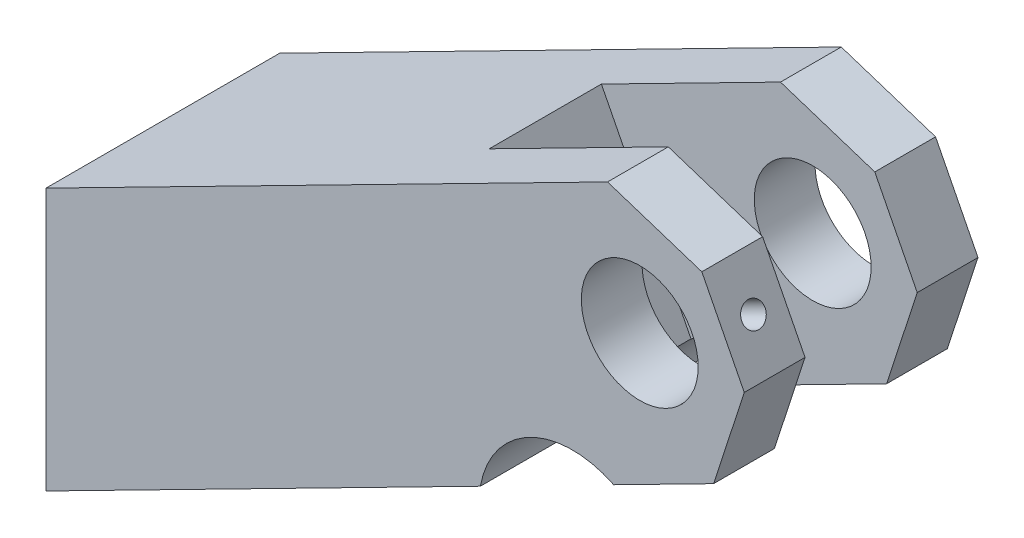
SolidWorks part; units mm, degrees
material "Masterteil Geometrie"
ref_plane "Vorne" through (0, 0, 0) normal (0, 0, 1) x (1, 0, 0)
ref_plane "Oben" through (0, 0, 0) normal (0, 1, 0) x (1, 0, 0)
ref_plane "Rechts" through (0, 0, 0) normal (1, 0, 0) x (0, 0, -1)
sketch "Skizze1" plane through (0, 0, 0) normal (0, 0, 1) x (1, 0, 0)
  line L0 (0, 0) -> (120.1288, 61.2087)
  line L1 (120.1288, 61.2087) -> (140.3038, 54.6535)
  line L2 (140.3038, 54.6535) -> (149.3836, 36.8333)
  line L3 (149.3836, 36.8333) -> (142.8283, 16.6584)
  line L4 (142.8283, 16.6584) -> (121.4442, 5.7626)
  line L5 (92.932, -8.7651) -> (0, -56.1163)
  line L6 (0, -56.1163) -> (0, 0)
  arc A0 (121.4442, 5.7626) -> (92.932, -8.7651) centre (112.636, -12.1933) ccw
  dimension "D3" = 20
  dimension "D4" = 8
  dimension "D9" = 55
  dimension "D1" = 45
  dimension "D2" = 45
  dimension "D5" = 63
  dimension "D6" = 15
  dimension "D7" = 15
  dimension "D8" = 50
  dimension "D10" = 175.3
extrude "Aufsatz-Linear austragen1" add sketch "Skizze1" along normal mid plane 50
sketch "Skizze2" plane through (0, 0, 0) normal (0, 0, 1) x (1, 0, 0)
  line L0 (133.4939, 68.0185) -> (81.8155, 41.6871)
  line L1 (120.1288, 61.2087) -> (0, 0) construction
  line L2 (81.8155, 41.6871) -> (104.5151, -2.8632)
  line L3 (104.5151, -2.8632) -> (156.1934, 23.4682)
  line L4 (156.1934, 23.4682) -> (133.4939, 68.0185)
  line L5 (149.3836, 36.8333) -> (140.3038, 54.6535) construction
  line L6 (121.4442, 5.7626) -> (142.8283, 16.6584) construction
  dimension "D1" = 58
extrude "Schnitt-Linear austragen1" cut sketch "Skizze2" against normal mid plane 24
hole_wizard "Ø25.0 (25) Durchmesser Bohrung1" positions "Skizze3" profile "Skizze4" hole size "Ø25.0" standard "Gabler-Normteile" end condition through all
sketch "Skizze3" plane through (0, 0, 25) normal (0, 0, 1) x (1, 0, 0)
  line L0 (149.3836, 36.8333) -> (140.3038, 54.6535) construction
  line L1 (144.8437, 45.7434) -> (127.0236, 36.6636) construction
  point P0 (127.0236, 36.6636)
  dimension "D1" = 20
sketch "Skizze4" plane through (127.0236, 36.6636, 25) normal (1, 0, 0) x (0, -1, 0)
  line L0 (0, 0) -> (0, 50)
  line L1 (0, 50) -> (12.5, 50)
  line L2 (12.5, 50) -> (12.5, 0)
  line L5 (12.5, 0) -> (0, 0)
  line L11 (0, -6.35) -> (0, 107.95) construction
  dimension "Bohrerdurchmesser" = 25
  dimension "Bohrungstiefe" = 50
hole_wizard "M6 Gewindebohrung1" positions "Skizze5" profile "Skizze7" tap size "M6" standard "Gabler-Normteile"
sketch "Skizze5" plane through (133.4939, 68.0185, 0) normal (0.891, 0.454, 0) x (0, 0, -1)
  line L0 (-25, -15) -> (-12, -15) construction
  line L1 (-25, -35) -> (-25, -15) construction
  point P0 (-18.5, -25)
  point P6 (-18.5, -15)
  point P9 (-25, -25)
sketch "Skizze7" plane through (144.8437, 45.7434, 18.5) normal (0, 0, 1) x (-0.454, 0.891, 0)
  line L0 (0, 0) -> (0, 18.5022)
  line L1 (0, 18.5022) -> (2.5, 17)
  line L2 (2.5, 17) -> (2.5, 0)
  line L5 (2.5, 0) -> (0, 0)
  line L10 (0, 18.5022) -> (-2.5, 17) construction
  line L11 (0, -6.35) -> (0, 107.95) construction
  dimension "Bohrerdurchmesser" = 5
  dimension "Bohrungstiefe" = 17
  dimension "Spitzenwinkel" = 118
cosmetic thread "Bohrungsgewinde1" parameters "D1"=7.7526, "D2"=6
hole_wizard "M12 Gewindebohrung1" positions "Skizze8" profile "Skizze9" tap size "M12" standard "Gabler-Normteile"
sketch "Skizze8" plane through (0, 0, 0) normal (-1, 0, 0) x (0, 0, 1)
  line L0 (0, 0) -> (0, -23.4984) construction
  line L2 (25, 0) -> (-25, 0) construction
  point P0 (-12.5, -12)
  point P2 (12.5, -12)
  point P4 (0, -32)
  dimension "D1" = 25
  dimension "D2" = 12
  dimension "D3" = 20
sketch "Skizze9" plane through (0, -12, -12.5) normal (0, 1, 0) x (0, 0, 1)
  line L0 (0, 0) -> (0, 28.0644)
  line L1 (0, 28.0644) -> (5.1, 25)
  line L2 (5.1, 25) -> (5.1, 0)
  line L5 (5.1, 0) -> (0, 0)
  line L10 (0, 28.0644) -> (-5.1, 25) construction
  line L11 (0, -6.35) -> (0, 107.95) construction
  dimension "Bohrerdurchmesser" = 10.2
  dimension "Bohrungstiefe" = 25
  dimension "Spitzenwinkel" = 118
cosmetic thread "Bohrungsgewinde2" parameters "D1"=17, "D2"=12
cosmetic thread "Bohrungsgewinde3" parameters "D1"=17, "D2"=12
cosmetic thread "Bohrungsgewinde4" parameters "D1"=17, "D2"=12
